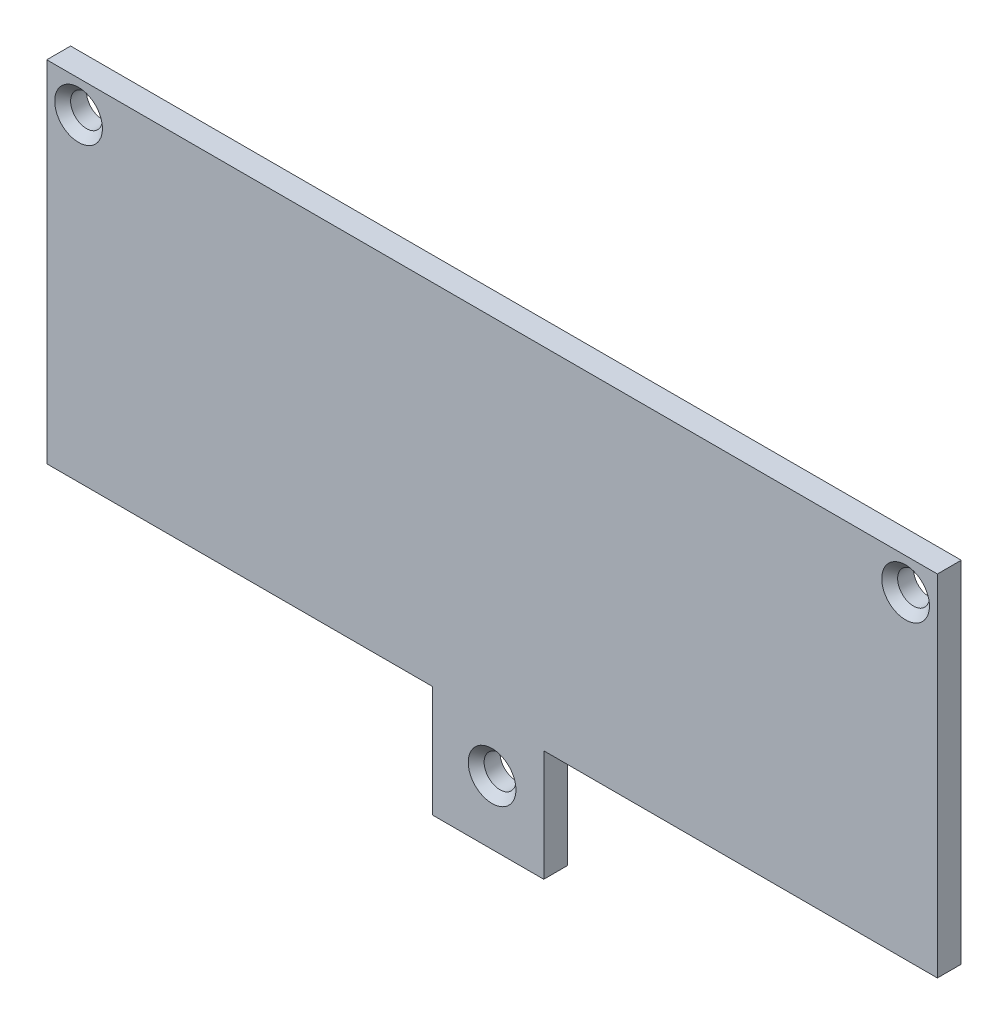
SolidWorks part; units mm, degrees
ref_plane "Спереди" through (0, 0, 0) normal (0, 0, 1) x (1, 0, 0)
ref_plane "Сверху" through (0, 0, 0) normal (0, 1, 0) x (1, 0, 0)
ref_plane "Справа" through (0, 0, 0) normal (1, 0, 0) x (0, 0, -1)
sketch "Эскиз1" plane through (0, 0, 0) normal (0, 0, 1) x (1, 0, 0)
  line L0 (25.5, 16) -> (25.5, 0) construction
  line L1 (0, 0) -> (51, 0)
  line L2 (0, 0) -> (0, 16)
  line L3 (0, 16) -> (51, 16)
  line L4 (51, 0) -> (51, 16)
  dimension "D1" = 51
  dimension "D2" = 16
extrude "Бобышка-Вытянуть1" add sketch "Эскиз1" along normal blind 1.5
sketch "Эскиз2" plane through (0, 0, 1.5) normal (0, 0, 1) x (1, 0, 0)
  line L0 (3.5, 20) -> (47.5, 20)
  line L1 (0, 0) -> (51, 0) construction
  line L2 (-2.5, 19.5) -> (-2.5, -2)
  line L3 (-2.5, -2) -> (21.75, -2)
  line L4 (53.5, 19.5) -> (53.5, -2)
  line L7 (51, 0) -> (51, 16) construction
  line L8 (25.25, 17.5) -> (25.25, -3) construction
  line L10 (28.75, -2) -> (53.5, -2)
  line L12 (3.5, 20) -> (-2.5, 20)
  line L13 (-2.5, 19.5) -> (-2.5, 20)
  line L15 (53.5, 19.5) -> (53.5, 20)
  line L16 (53.5, 20) -> (47.5, 20)
  line L18 (21.75, -2) -> (21.75, -9)
  line L19 (21.75, -9) -> (28.75, -9)
  line L20 (28.75, -2) -> (28.75, -9)
  dimension "D1" = 2
  dimension "D2" = 3.5
  dimension "D3" = 56
  dimension "D4" = 2.5
  dimension "D5" = 22
  dimension "D9" = 3.5
  dimension "D10" = 7
extrude "Бобышка-Вытянуть2" add sketch "Эскиз2" along normal blind 1.5
sketch "Эскиз4" plane through (0, 0, 3) normal (0, 0, 1) x (1, 0, 0)
  line L0 (55.8336, 19) -> (-8.1228, 19) construction
  line L3 (25.5, 20) -> (25.5, 12.0735) construction
  line L4 (53.5, 20) -> (-2.5, 20) construction
  line L5 (0, 16) -> (51, 16) construction
  line L8 (25.5, 20) -> (25.5, 11.3543) construction
  line L9 (53.5, 20) -> (-2.5, 20) construction
  line L12 (32.4257, -5) -> (9.5045, -5) construction
  line L13 (0, 0) -> (51, 0) construction
  line L14 (25.5, 0) -> (25.5, -10.9505) construction
  dimension "D1" = 3
  dimension "D2" = 5
fillet "Скругление2" radius 3 4 edges at (0, 16, 0.75) (0, 0, 0.75) (51, 0, 0.75) (51, 16, 0.75)
ref_point "Точка1"
ref_point "Точка2"
ref_point "Точка3"
hole_wizard "Зенковка для  винта с полупотайной головкой M21" positions "Эскиз8" profile "Эскиз7" countersink size "M2" standard "Ansi Metric" end condition through all
sketch "Эскиз8" plane through (0, 0, 3) normal (0, 0, 1) x (1, 0, 0)
  line L0 (53.5, 20) -> (-2.5, 20) construction
  line L1 (-2.5, 20) -> (-2.5, -2) construction
  line L2 (53.5, -2) -> (53.5, 20) construction
  point P3 (25.5, -5)
  point P11 (-0.5, 18)
  point P13 (51.5, 18)
  dimension "D1" = 2
  dimension "D2" = 2
  dimension "D3" = 2
  dimension "D4" = 2
sketch "Эскиз7" plane through (25.5, -5, 3) normal (1, 0, 0) x (0, -1, 0)
  line L0 (0, 0) -> (0, 3)
  line L1 (0, 3) -> (1, 3)
  line L2 (1, 3) -> (1, 0.5)
  line L3 (1, 0.5) -> (1.5, 0)
  line L5 (1.5, 0) -> (0, 0)
  line L6 (-1, 0.5) -> (-1.5, 0) construction
  line L11 (0, -6.35) -> (0, 107.95) construction
  dimension "Диаметр сквозного отверстия" = 2
  dimension "Глубина сквозного отверстия" = 3
  dimension "Диаметр передней зенковки" = 3
  dimension "Угол передней зенковки" = 90
